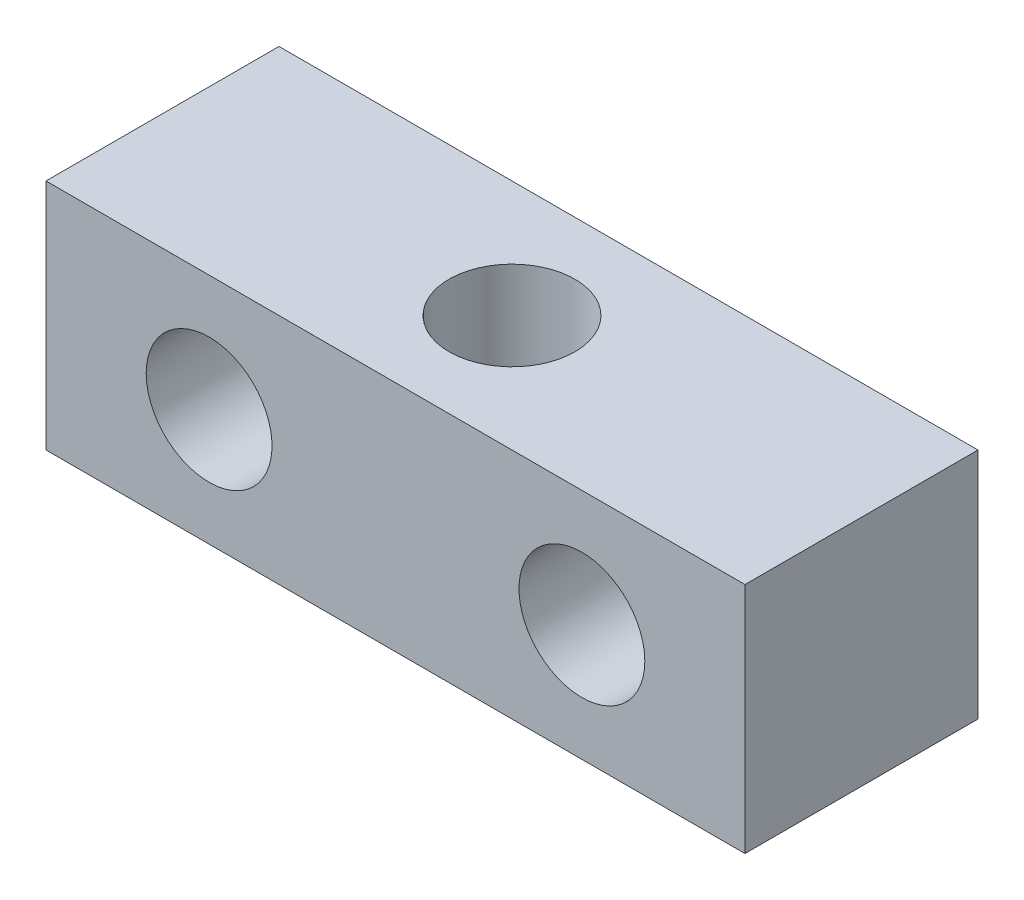
SolidWorks part; units mm, degrees
ref_plane "Front Plane" through (0, 0, 0) normal (0, 0, 1) x (1, 0, 0)
ref_plane "Top Plane" through (0, 0, 0) normal (0, 1, 0) x (1, 0, 0)
ref_plane "Right Plane" through (0, 0, 0) normal (1, 0, 0) x (0, 0, -1)
sketch "Sketch1" plane through (0, 0, 0) normal (0, 0, 1) x (1, 0, 0)
  line L1 (-19.05, -6.35) -> (19.05, -6.35)
  line L2 (-19.05, -6.35) -> (-19.05, 6.35)
  line L3 (-19.05, 6.35) -> (19.05, 6.35)
  line L4 (19.05, -6.35) -> (19.05, 6.35)
  line L5 (-19.05, -6.35) -> (19.05, 6.35) construction
  line L6 (-19.05, 6.35) -> (19.05, -6.35) construction
  point P0 (0, 0)
  dimension "D1" = 12.7
  dimension "D2" = 38.1
extrude "Boss-Extrude1" add sketch "Sketch1" along normal blind 12.7
sketch "Sketch2" plane through (0, 0, 12.7) normal (0, 0, 1) x (1, 0, 0)
  circle A0 centre (10.16, 0) radius 3.429
  point P2 (0, 0)
  dimension "D2" = 6.858
  dimension "D1" = 10.16
extrude "Cut-Extrude1" cut sketch "Sketch2" against normal blind 12.7
sketch "Sketch3" plane through (0, 6.35, 0) normal (0, 1, 0) x (1, 0, 0)
  line L1 (19.05, -12.7) -> (19.05, 0) construction
  line L2 (19.05, -6.35) -> (11.9475, -6.35) construction
  circle A0 centre (0, -6.35) radius 3.429
  point P2 (0, 0)
  dimension "D1" = 6.858
extrude "Cut-Extrude2" cut sketch "Sketch3" against normal blind 12.7 contours A0
mirror "Mirror1" about plane through (0, 0, 0) normal (1, 0, 0) of "Cut-Extrude1"
